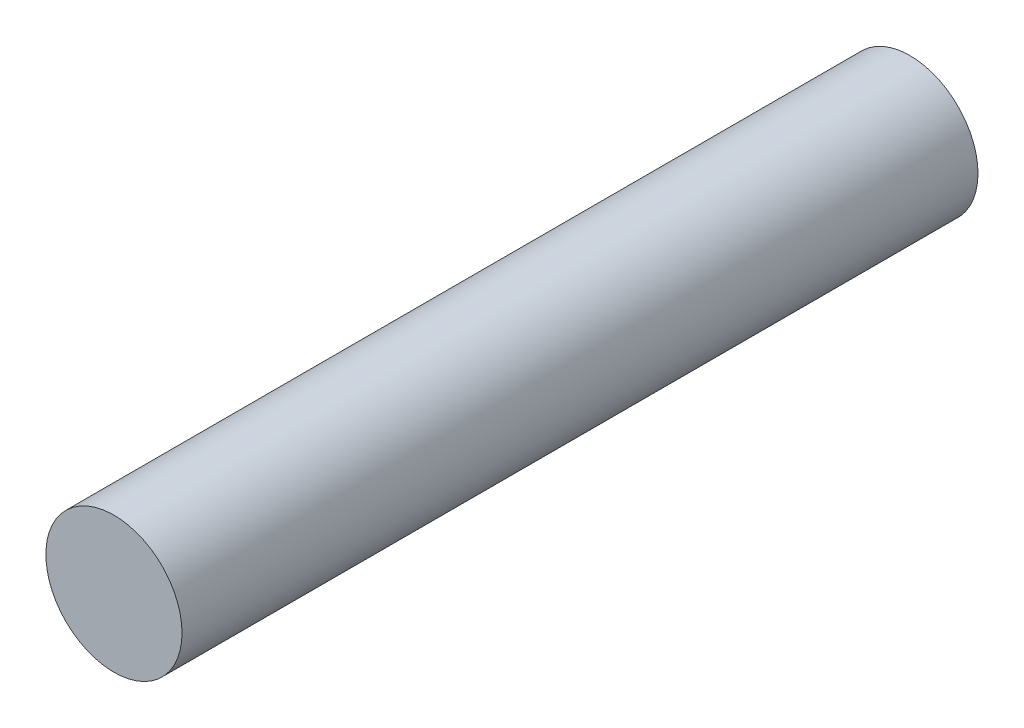
SolidWorks part; units mm, degrees
ref_plane "Front Plane" through (0, 0, 0) normal (0, 0, 1) x (1, 0, 0)
ref_plane "Top Plane" through (0, 0, 0) normal (0, 1, 0) x (1, 0, 0)
ref_plane "Right Plane" through (0, 0, 0) normal (1, 0, 0) x (0, 0, -1)
sketch "Sketch2" plane through (0, 0, 0) normal (0, 0, 1) x (1, 0, 0)
  circle A0 centre (0, 0) radius 6.5
  dimension "D1" = 13
extrude "Boss-Extrude1" add sketch "Sketch2" along normal blind 76
